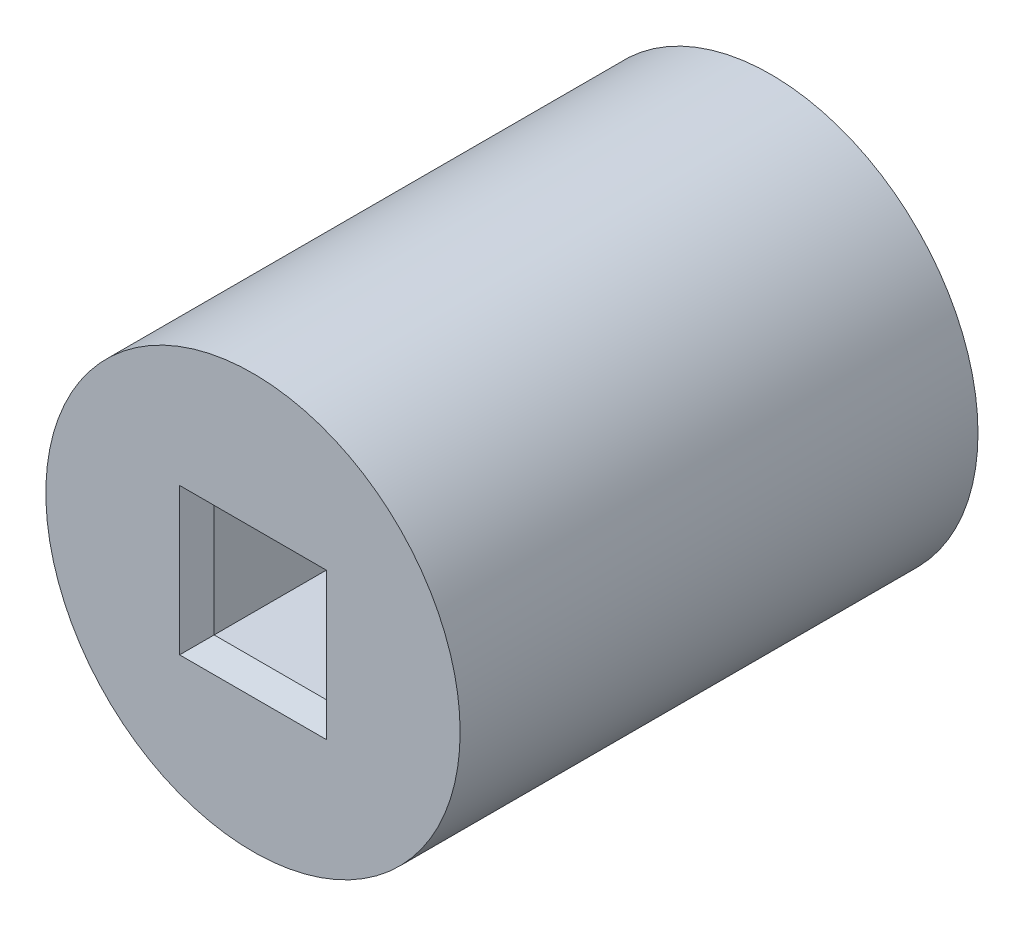
SolidWorks part; units mm, degrees
ref_plane "Front Plane" through (0, 0, 0) normal (0, 0, 1) x (1, 0, 0)
ref_plane "Top Plane" through (0, 0, 0) normal (0, 1, 0) x (1, 0, 0)
ref_plane "Right Plane" through (0, 0, 0) normal (1, 0, 0) x (0, 0, -1)
sketch "Sketch1" plane through (0, 0, 0) normal (0, 0, 1) x (1, 0, 0)
  circle A0 centre (0, 0) radius 6
  circle A1 centre (0, 0) radius 2.25 construction
  dimension "D1" = 12
  dimension "D2" = 4.5
extrude "Boss-Extrude1" add sketch "Sketch1" along normal blind 15
sketch "Sketch2" plane through (0, 0, 0) normal (0, 0, -1) x (-1, 0, 0)
  circle A0 centre (0, 0) radius 2.6
  dimension "D1" = 5.2
extrude "Cut-Extrude1" cut sketch "Sketch2" against normal blind 10
sketch "Sketch5" plane through (0, 0, 15) normal (0, 0, 1) x (1, 0, 0)
  line L1 (-1.625, 1.625) -> (1.625, 1.625)
  line L2 (-1.625, 1.625) -> (-1.625, -1.625)
  line L3 (-1.625, -1.625) -> (1.625, -1.625)
  line L4 (1.625, 1.625) -> (1.625, -1.625)
  line L5 (-1.625, 1.625) -> (1.625, -1.625) construction
  line L6 (-1.625, -1.625) -> (1.625, 1.625) construction
  point P0 (0, 0)
  dimension "D1" = 3.25
  dimension "D2" = 3.25
extrude "Cut-Extrude2" cut sketch "Sketch5" against normal blind 5
chamfer "Chamfer1" distance 0.5 angle 45 5 edges at (1.625, 0, 15) (0, 1.625, 15) (-1.625, 0, 15) (0, -1.625, 15) (-2.6, 0, 0)
